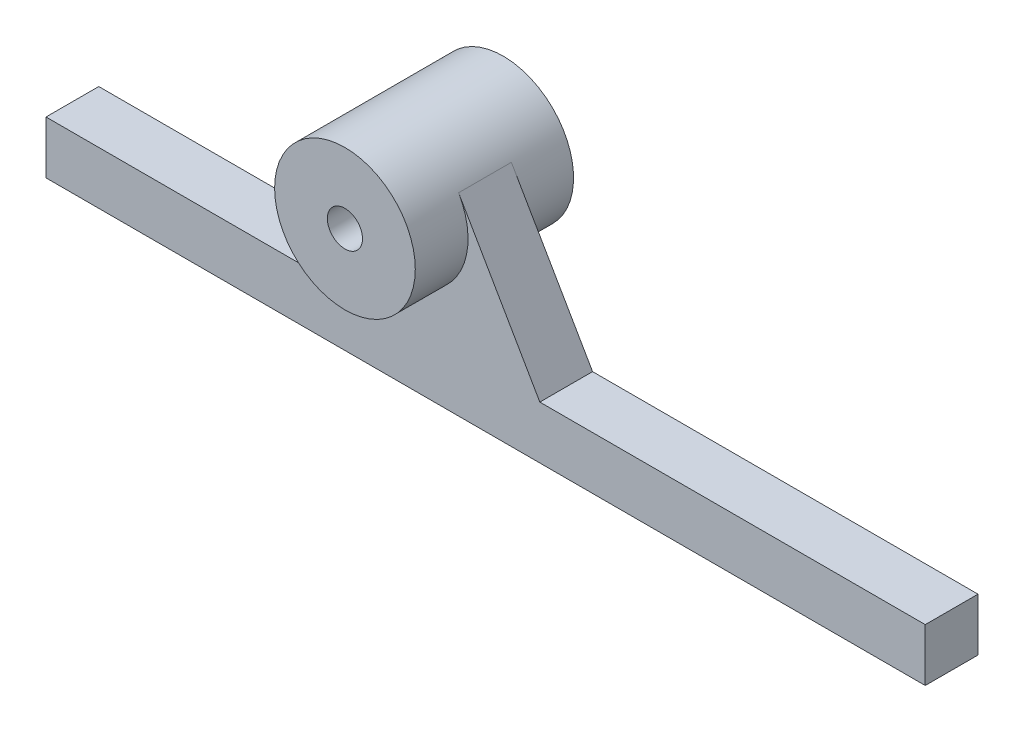
SolidWorks part; units mm, degrees
ref_plane "前视基准面" through (0, 0, 0) normal (0, 0, 1) x (1, 0, 0)
ref_plane "上视基准面" through (0, 0, 0) normal (0, 1, 0) x (1, 0, 0)
ref_plane "右视基准面" through (0, 0, 0) normal (1, 0, 0) x (0, 0, -1)
sketch "草图1" plane through (0, 0, 0) normal (0, 0, 1) x (1, 0, 0)
  line L0 (-100, 0) -> (150, 0)
  line L1 (150, 0) -> (150, 15)
  line L2 (150, 15) -> (40.4145, 15)
  line L3 (-100, 15) -> (-100, 0)
  line L4 (0, 0) -> (0, 67.4348) construction
  line L5 (-19.6962, 48.473) -> (-25.5983, 15)
  line L6 (17.3205, 55) -> (40.4145, 15)
  line L7 (-25.5983, 15) -> (-100, 15)
  arc A0 (17.3205, 55) -> (-19.6962, 48.473) centre (0, 45) ccw
  circle A1 centre (0, 45) radius 5
  dimension "D3" = 10
  dimension "D4" = 40
  dimension "D1" = 15
  dimension "D2" = 250
  dimension "D5" = 80
  dimension "D6" = 120
  dimension "D7" = 30
  dimension "D8" = 100
extrude "凸台-拉伸1" add sketch "草图1" along normal blind 15
sketch "草图2" plane through (0, 0, 15) normal (0, 0, 1) x (1, 0, 0)
  circle A0 centre (0, 45) radius 20
  circle A1 centre (0, 45) radius 5 construction
  circle A2 centre (0, 45) radius 5
  dimension "D1" = 40
extrude "凸台-拉伸2" add sketch "草图2" along normal blind 15
sketch "草图3" plane through (0, 0, 0) normal (0, 0, -1) x (-1, 0, 0)
  circle A0 centre (0, 45) radius 20
  circle A1 centre (0, 45) radius 5 construction
  circle A2 centre (0, 45) radius 5
  dimension "D1" = 40
extrude "凸台-拉伸3" add sketch "草图3" along normal blind 15
